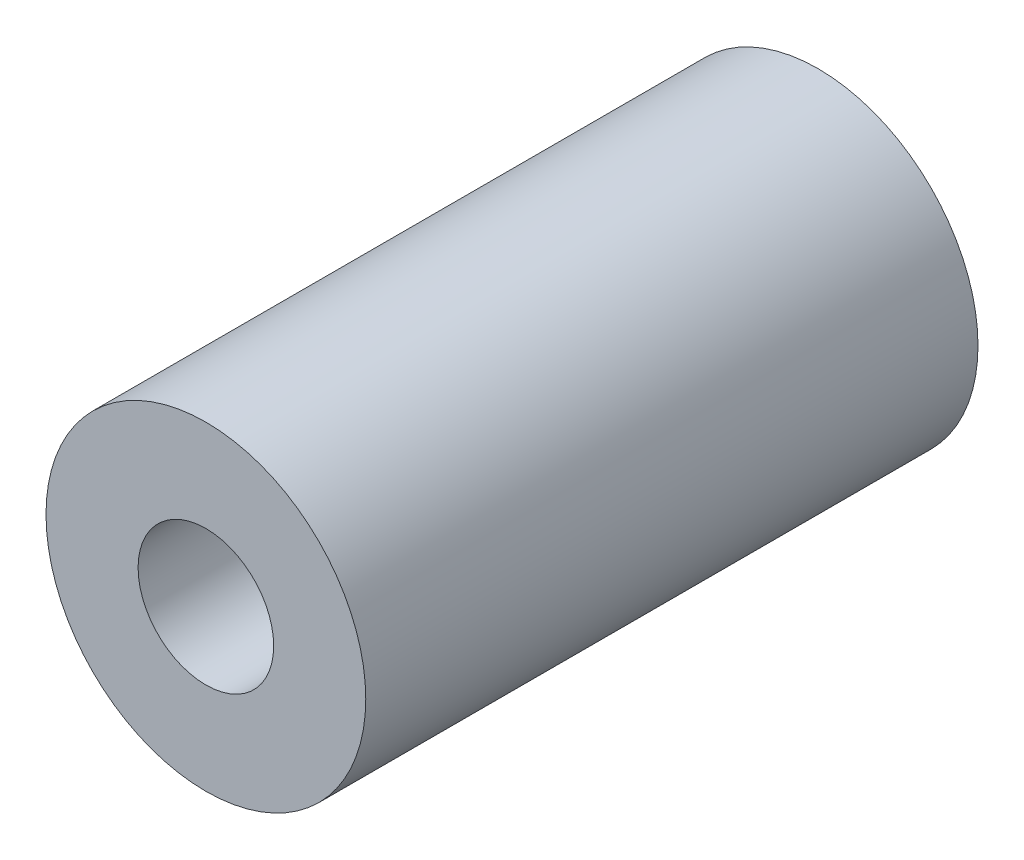
SolidWorks part; units mm, degrees
material "6061-T6 (SS)"
ref_plane "Front Plane" through (0, 0, 0) normal (0, 0, 1) x (1, 0, 0)
ref_plane "Top Plane" through (0, 0, 0) normal (0, 1, 0) x (1, 0, 0)
ref_plane "Right Plane" through (0, 0, 0) normal (1, 0, 0) x (0, 0, -1)
sketch "Sketch1" plane through (0, 0, 0) normal (0, 0, 1) x (1, 0, 0)
  circle A0 centre (0, 0) radius 4.7625
  dimension "D1" = 9.525
extrude "Boss-Extrude1" add sketch "Sketch1" along normal mid plane 18.2372
hole_wizard "#10-32 Tapped Hole2" positions "3DSketch1" profile "Sketch4" tap size "#10-32" standard "ANSI Inch"
sketch3d "3DSketch1"
  line L0 (0, 0, 9.1186) -> (0, 0, -9.1186) construction
  point P0 (0, 0, 9.1186)
  point P4 (0, 0, -9.1186)
sketch "Sketch4" plane through (0, 0, 9.1186) normal (1, 0, 0) x (0, -1, 0)
  line L0 (0, 0) -> (0, 16.2908)
  line L1 (0, 16.2908) -> (2.0193, 15.0774)
  line L2 (2.0193, 15.0774) -> (2.0193, 0)
  line L5 (2.0193, 0) -> (0, 0)
  line L10 (0, 16.2908) -> (-2.0193, 15.0774) construction
  line L11 (0, -6.35) -> (0, 107.95) construction
  dimension "Tap Drill Dia." = 4.0386
  dimension "Tap Drill Depth" = 15.0774
  dimension "Drill Angle" = 118
cosmetic thread "Hole Thread2" parameters "D1"=12.7, "D2"=4.826
cosmetic thread "Hole Thread3" parameters "D1"=12.7, "D2"=4.826
